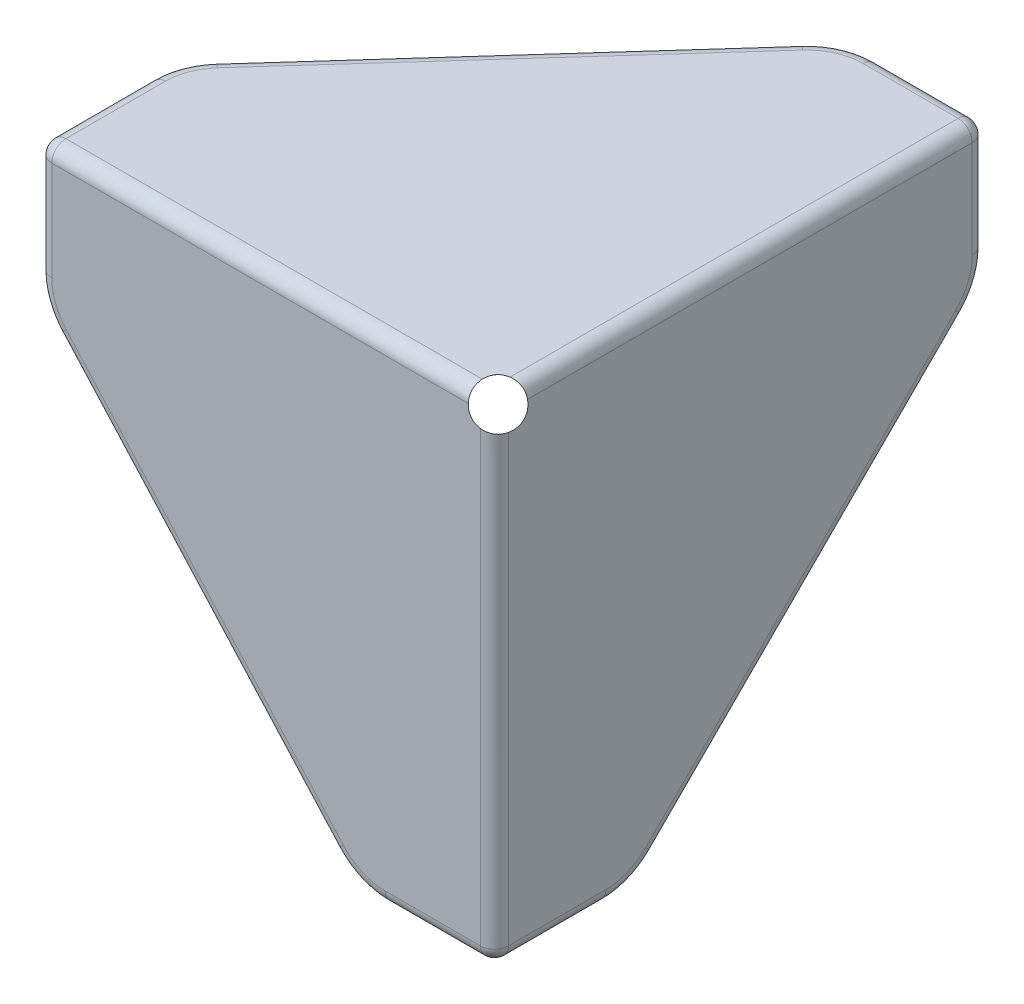
SolidWorks part; units mm, degrees
other "Marcação2"
sketch "Esboço9" plane through (-22.5, 22.5, -33) normal (-0.1173, 0.0482, -0.9919) x (-0.5451, -0.838, 0.0238)
ref_plane "Plano frontal" through (0, 0, 0) normal (0, 0, 1) x (1, 0, 0)
ref_plane "Plano superior" through (0, 0, 0) normal (0, 1, 0) x (1, 0, 0)
ref_plane "Plano direito" through (0, 0, 0) normal (1, 0, 0) x (0, 0, -1)
sketch "Esboço1" plane through (0, 0, 0) normal (0, 0, 1) x (1, 0, 0)
  line L0 (7.2546, -29.3511) -> (-37.7454, 20.6489)
  line L1 (-37.7454, 40.6489) -> (27.2546, 40.6489)
  line L2 (-37.7454, 40.6489) -> (-37.7454, 20.6489)
  line L3 (7.2546, -29.3511) -> (27.2546, -29.3511)
  line L4 (27.2546, 40.6489) -> (27.2546, -29.3511)
  line L5 (-37.7454, 40.6489) -> (27.2546, -29.3511) construction
  line L6 (-8.186, -12.2091) -> (27.2546, 40.6489) construction
  point P0 (0, 0)
  dimension "D1" = 65
  dimension "D2" = 70
  dimension "D3" = 20
  dimension "D4" = 20
extrude "Ressalto-extrusão1" add sketch "Esboço1" along normal blind 12
sketch "Esboço2" plane through (0, 40.6489, 0) normal (0, 1, 0) x (1, 0, 0)
  line L0 (7.2546, 58) -> (-37.7454, 8)
  line L1 (27.2546, -12) -> (-37.7454, -12)
  line L2 (27.2546, -12) -> (27.2546, 58)
  line L3 (27.2546, 58) -> (7.2546, 58)
  line L4 (-37.7454, -12) -> (-37.7454, 8)
  dimension "D1" = 70
  dimension "D2" = 65
  dimension "D3" = 20
  dimension "D4" = 20
extrude "Ressalto-extrusão2" add sketch "Esboço2" against normal blind 12
sketch "Esboço3" plane through (27.2546, 0, 0) normal (1, 0, 0) x (0, 0, -1)
  line L0 (58, 20.6489) -> (8, -29.3511)
  line L1 (-12, 40.6489) -> (58, 40.6489)
  line L2 (-12, 40.6489) -> (-12, -29.3511)
  line L3 (-12, -29.3511) -> (8, -29.3511)
  line L4 (58, 40.6489) -> (58, 20.6489)
  dimension "D1" = 70
  dimension "D2" = 70
  dimension "D3" = 20
  dimension "D4" = 20
extrude "Ressalto-extrusão3" add sketch "Esboço3" against normal blind 12
fillet "Filete1" radius 10 6 edges at (-37.7454, 34.6489, -8) (-37.7454, 20.6489, 6) (7.2546, -29.3511, 6) (21.2546, -29.3511, -8) (7.2546, 34.6489, -58) (21.2546, 20.6489, -58)
fillet "Filete2" radius 2 18 edges at (-37.7454, 32.5675, 12) (-37.0816, 20.9036, 12) (-15.4515, -4.1221, 12) (7.6399, -28.4861, 12) (19.4814, -29.3511, 12) (27.2546, 5.6489, 12) (27.2546, -29.3511, 4.0711) (27.2546, -28.5899, -7.6847) (27.2546, -4.3511, -33) (27.2546, 20.9642, -57.2388) (27.2546, 32.7199, -58) (27.2546, 40.6489, -23) (-5.2454, 40.6489, 12) (-37.7454, 40.6489, 3.9187) (7.6399, 40.6489, -57.135) (-37.0816, 40.6489, -7.7453) (-15.4515, 40.6489, -32.771) (19.4814, 40.6489, -58)
fillet "Filete3" radius 2 3 edges at (-11.2454, 28.6489, 0) (15.2546, -0.3511, 0) (15.2546, 28.6489, -29)
sketch "Esboço10" plane through (0, 0, -58) normal (0, 0, -1) x (-1, 0, 0)
  line L0 (-14.6688, 28.0631) -> (-25.2546, 38.6489) construction
  line L1 (-25.2546, 9.9142) -> (-9.9142, 38.6489) construction
  line L2 (-25.2546, 38.6489) -> (-25.2546, 24.791) construction
  line L3 (-11.7083, 38.6489) -> (-25.2546, 38.6489) construction
  arc A0 (-13.2546, 28.6489) -> (-15.2546, 26.6489) centre (-13.2546, 26.6489) ccw construction
  circle A1 centre (-19.9617, 33.356) radius 3.1
  dimension "D1" = 6.2
sketch "Esboço11" plane through (-37.7454, 0, 0) normal (-1, 0, 0) x (0, 0, 1)
  line L0 (-0.5858, 28.0631) -> (10, 38.6489) construction
  line L1 (10, 9.9142) -> (-18.7346, 38.6489) construction
  line L2 (10, 24.4862) -> (10, 38.6489) construction
  line L3 (10, 38.6489) -> (-4.1626, 38.6489) construction
  arc A0 (0, 26.6489) -> (-2, 28.6489) centre (-2, 26.6489) ccw construction
  circle A1 centre (4.7071, 33.356) radius 3.1
  dimension "D1" = 6.2
sketch "Esboço12" plane through (0, -29.3511, 0) normal (0, -1, 0) x (1, 0, 0)
  line L0 (14.6688, -0.5858) -> (25.2546, 10) construction
  line L1 (25.2546, 10) -> (9.9142, 10) construction
  line L2 (25.2546, 10) -> (11.7083, 10) construction
  line L3 (9.9142, 10) -> (19.9142, 0) construction
  arc A0 (15.2546, -2) -> (13.2546, 0) centre (13.2546, -2) ccw construction
  circle A1 centre (19.9617, 4.7071) radius 3.1
  dimension "D1" = 6.2
extrude "Corte-extrusão4" cut sketch "Esboço11" against normal blind 40 contours A1
extrude "Corte-extrusão5" cut sketch "Esboço12" against normal blind 40 contours A1
extrude "Corte-extrusão6" cut sketch "Esboço10" against normal blind 40 contours A1
ref_plane "Plano1" through (25.3012, 25.3012, 25.3012) normal (0.5774, 0.5774, 0.5774) x (0.8165, -0.4082, -0.4082)
sketch "Esboço15" plane through (25.3012, 25.3012, 25.3012) normal (0.5774, 0.5774, 0.5774) x (0.8165, -0.4082, -0.4082)
  line L0 (-0.057, 18.8436) -> (-49.8633, 18.8436) construction
  circle A0 centre (1.1886, 20.2586) radius 3
  dimension "D1" = 6
  dimension "D2" = 1.415
extrude "Corte-extrusão8" cut sketch "Esboço15" against normal blind 30 and the other way blind 10
